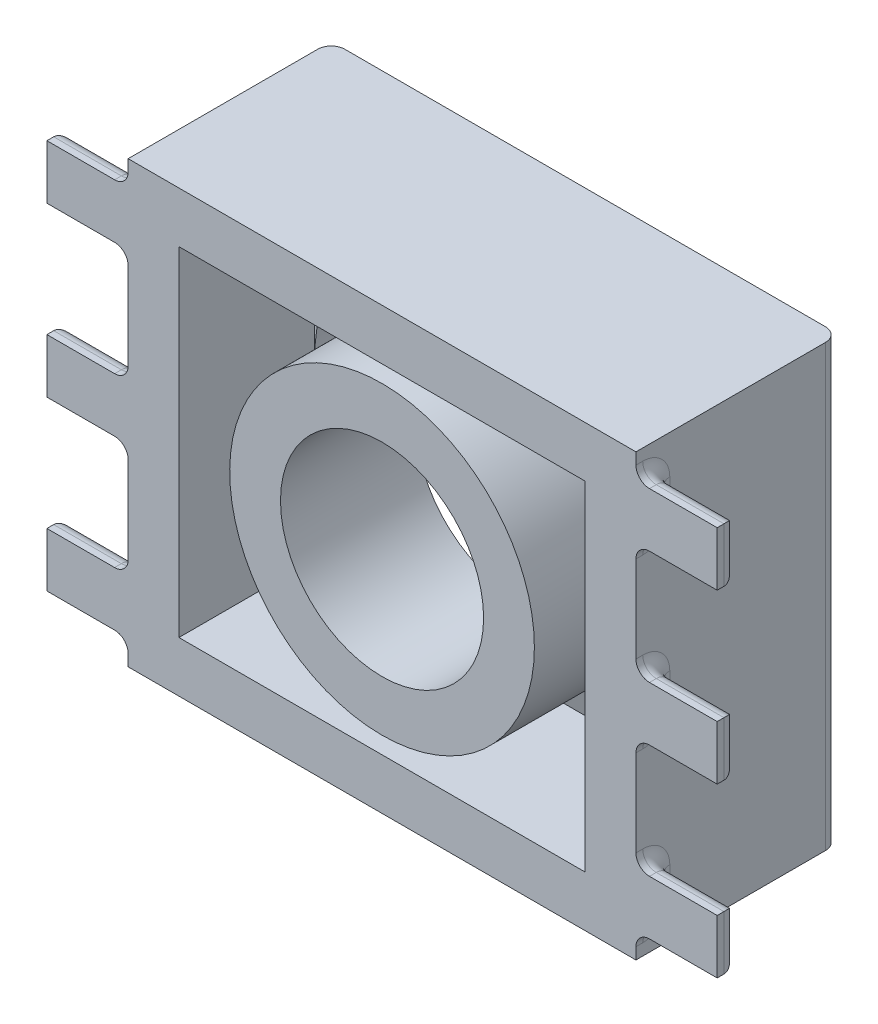
SolidWorks part; units mm, degrees
ref_plane "前视基准面" through (0, 0, 0) normal (0, 0, 1) x (1, 0, 0)
ref_plane "上视基准面" through (0, 0, 0) normal (0, 1, 0) x (1, 0, 0)
ref_plane "右视基准面" through (0, 0, 0) normal (1, 0, 0) x (0, 0, -1)
sketch "草图1" plane through (0, 0, 0) normal (0, 0, 1) x (1, 0, 0)
  line L1 (-3.75, -3.25) -> (3.75, -3.25)
  line L2 (-3.75, -3.25) -> (-3.75, 3.25)
  line L3 (-3.75, 3.25) -> (3.75, 3.25)
  line L4 (3.75, -3.25) -> (3.75, 3.25)
  line L5 (-3.75, -3.25) -> (3.75, 3.25) construction
  line L6 (-3.75, 3.25) -> (3.75, -3.25) construction
  point P0 (0, 0)
  dimension "D1" = 7.5
  dimension "D2" = 6.5
extrude "凸台-拉伸1" add sketch "草图1" along normal blind 3
ref_plane "基准面4" through (0, 0, 3) normal (0, 0, 1) x (1, 0, 0)
sketch "草图2" plane through (0, 0, 3) normal (0, 0, 1) x (1, 0, 0)
  line L1 (-3, -2.5) -> (3, -2.5)
  line L2 (-3, -2.5) -> (-3, 2.5)
  line L3 (-3, 2.5) -> (3, 2.5)
  line L4 (3, -2.5) -> (3, 2.5)
  line L5 (-3, -2.5) -> (3, 2.5) construction
  line L6 (-3, 2.5) -> (3, -2.5) construction
  point P0 (0, 0)
  dimension "D1" = 6
  dimension "D2" = 5
extrude "切除-拉伸1" cut sketch "草图2" against normal blind 2
ref_plane "基准面5" through (0, 0, 2) normal (0, 0, 1) x (1, 0, 0)
sketch "草图3" plane through (0, 0, 2) normal (0, 0, 1) x (1, 0, 0)
  circle A0 centre (0, 0) radius 2.25
  dimension "D1" = 4.5
extrude "凸台-拉伸2" add sketch "草图3" along normal mid plane 2
sketch "草图4" plane through (0, 0, 2) normal (0, 0, 1) x (1, 0, 0)
  circle A0 centre (0, 0) radius 1.5
  dimension "D1" = 3
extrude "切除-拉伸2" cut sketch "草图4" against normal mid plane 2
ref_plane "基准面6" through (-3.75, 0, 0) normal (-1, 0, 0) x (0, 0, 1)
sketch "草图6" plane through (0, 0, 0) normal (0, 0, -1) x (-1, 0, 0)
  line L0 (0, -1000) -> (0, 49000) construction
sketch "草图8" plane through (0, 0, 0) normal (0, 0, -1) x (-1, 0, 0)
  line L0 (-0.5692, -2.9455) -> (-0.5692, 2.9455)
  line L3 (0, -1000) -> (0, 49000) construction
  line L5 (0.5692, -2.9455) -> (0.5692, 2.9455)
  arc A0 (0.5692, -2.9455) -> (0.5692, 2.9455) centre (0, 0) ccw
  arc A1 (-0.5692, 2.9455) -> (-0.5692, -2.9455) centre (0, 0) ccw
extrude "切除-拉伸5" cut sketch "草图8" against normal blind 1
sketch "草图9" plane through (3.75, 0, 0) normal (1, 0, 0) x (0, 0, -1)
  line L0 (-1000, 0) -> (49000, 0) construction
  line L1 (-3, 3.575) -> (-3, -3.575) construction
  line L2 (-3, 2.88) -> (-2.7, 2.88)
  line L3 (-3, 2.88) -> (-3, 2.08)
  line L4 (-3, 2.08) -> (-2.7, 2.08)
  line L5 (-2.7, 2.88) -> (-2.7, 2.08)
  line L6 (-3, 3.25) -> (0, 3.25) construction
  line L7 (-3, -2.08) -> (-2.7, -2.08)
  line L8 (-2.7, -2.88) -> (-2.7, -2.08)
  line L9 (-3, -2.88) -> (-2.7, -2.88)
  line L10 (-3, -2.88) -> (-3, -2.08)
  line L12 (-3, 0.4) -> (-2.7, 0.4)
  line L13 (-3, 0.4) -> (-3, -0.4)
  line L14 (-3, -0.4) -> (-2.7, -0.4)
  line L15 (-2.7, 0.4) -> (-2.7, -0.4)
  dimension "D1" = 0.37
  dimension "D2" = 0.8
  dimension "D3" = 0.3
  dimension "D4" = 0.8
  dimension "D5" = 0.4
  dimension "D6" = 0.3
extrude "凸台-拉伸5" add sketch "草图9" along normal blind 1.2
sketch "草图11" plane through (-3.75, 0, 0) normal (-1, 0, 0) x (0, 0, 1)
  line L0 (-1000, 0) -> (49000, 0) construction
  line L1 (3, -3.575) -> (3, 3.575) construction
  line L2 (3, 2.88) -> (2.7, 2.88)
  line L3 (3, 2.88) -> (3, 2.08)
  line L4 (3, 2.08) -> (2.7, 2.08)
  line L5 (2.7, 2.88) -> (2.7, 2.08)
  line L6 (3, 3.25) -> (0, 3.25) construction
  line L7 (3, -2.08) -> (2.7, -2.08)
  line L8 (2.7, -2.88) -> (2.7, -2.08)
  line L9 (3, -2.88) -> (2.7, -2.88)
  line L10 (3, -2.88) -> (3, -2.08)
  line L12 (3, 0.4) -> (2.7, 0.4)
  line L13 (3, 0.4) -> (3, -0.4)
  line L14 (3, -0.4) -> (2.7, -0.4)
  line L15 (2.7, 0.4) -> (2.7, -0.4)
  dimension "D1" = 0.37
  dimension "D2" = 0.8
  dimension "D3" = 0.3
  dimension "D4" = 0.8
  dimension "D5" = 0.4
  dimension "D6" = 0.3
extrude "凸台-拉伸6" add sketch "草图11" along normal blind 1.2
fillet "圆角4" radius 0.2 36 edges at (3.75, 2.08, 2.85) (3.75, 2.88, 2.85) (3.75, -0.4, 2.85) (3.75, 0.4, 2.85) (-3.75, -2.08, 2.85) (-3.75, -2.88, 2.85) (-3.75, 0.4, 2.85) (-3.75, -0.4, 2.85) (-3.75, 2.88, 2.85) (-3.75, 2.08, 2.85) (3.75, -2.88, 2.85) (3.75, -2.08, 2.85) (4.35, 2.08, 2.7) (4.95, 2.48, 2.7) (4.35, 2.88, 2.7) (3.75, 2.48, 2.7) (4.35, -0.4, 2.7) (4.95, 0, 2.7) (4.35, 0.4, 2.7) (3.75, 0, 2.7) (-4.35, -2.08, 2.7) (-4.95, -2.48, 2.7) (-4.35, -2.88, 2.7) (-3.75, -2.48, 2.7) (-4.35, 0.4, 2.7) (-4.95, 0, 2.7) (-4.35, -0.4, 2.7) (-3.75, 0, 2.7) (-4.35, 2.88, 2.7) (-4.95, 2.48, 2.7) (-4.35, 2.08, 2.7) (-3.75, 2.48, 2.7) (4.35, -2.88, 2.7) (4.95, -2.48, 2.7) (4.35, -2.08, 2.7) (3.75, -2.48, 2.7)
fillet "圆角5" radius 0.2 2 edges at (-3.75, 0, 0) (3.75, 0, 0)
